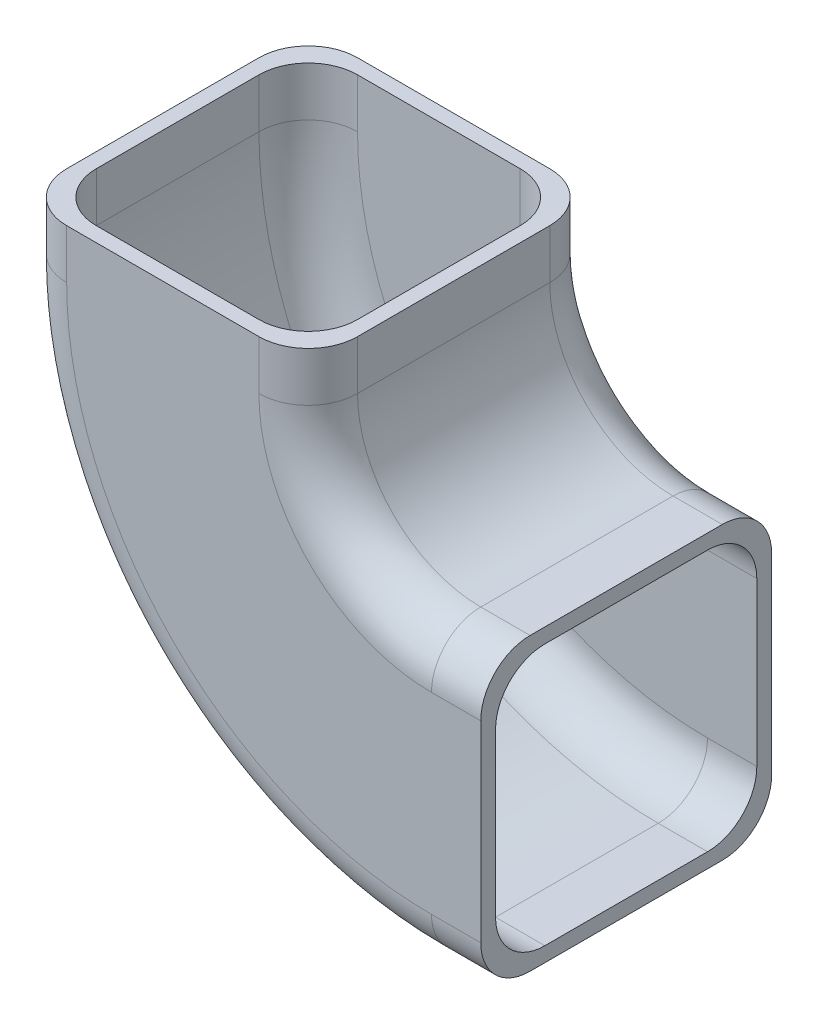
SolidWorks part; units mm, degrees
ref_plane "Front Plane" through (0, 0, 0) normal (0, 0, 1) x (1, 0, 0)
ref_plane "Top Plane" through (0, 0, 0) normal (0, 1, 0) x (1, 0, 0)
ref_plane "Right Plane" through (0, 0, 0) normal (1, 0, 0) x (0, 0, -1)
ref_plane "Plane1" through (0, 0, 26.5) normal (0, 0, 1) x (1, 0, 0)
sketch "Sketch3" plane through (0, 0, 0) normal (0, 0, 1) x (1, 0, 0)
  line L0 (-32.4349, -26.1886) -> (26.5651, -26.1886)
  line L1 (26.5651, -26.1886) -> (26.5651, -36.1886)
  line L2 (-32.4349, -26.1886) -> (-32.4349, -36.1886)
  line L3 (51.5651, -61.1886) -> (61.5651, -61.1886)
  line L4 (51.5651, -120.1886) -> (61.5651, -120.1886)
  line L5 (61.5651, -120.1886) -> (61.5651, -61.1886)
  arc A1 (26.5651, -36.1886) -> (51.5651, -61.1886) centre (51.5651, -36.1886) ccw
  arc A2 (-32.4349, -36.1886) -> (51.5651, -120.1886) centre (51.5651, -36.1886) ccw
  dimension "D3" = 10
  dimension "D1" = 59
  dimension "D2" = 10
extrude "Boss-Extrude3" add sketch "Sketch3" along normal blind 59
sketch "Sketch4" plane through (61.5651, 0, 0) normal (1, 0, 0) x (0, 0, -1)
  line L0 (0, 55) -> (0, -55) construction
  line L1 (-59, -61.1886) -> (0, -61.1886)
  line L2 (-59, -61.1886) -> (-59, -120.1886)
  line L3 (-59, -120.1886) -> (0, -120.1886)
  line L4 (0, -61.1886) -> (0, -120.1886)
  line L5 (-59, -120.1886) -> (0, -120.1886) construction
extrude "Boss-Extrude4" add sketch "Sketch4" along normal blind 100
shell "Shell2" thickness 3
sketch "Sketch5" plane through (161.5651, 0, 0) normal (1, 0, 0) x (0, 0, -1)
  line L5 (0, 55) -> (0, -55) construction
  line L6 (-59, -61.1886) -> (0, -61.1886)
  line L8 (-59, -61.1886) -> (-59, -120.1886)
  line L9 (-59, -120.1886) -> (0, -120.1886)
  line L10 (0, -61.1886) -> (0, -120.1886)
  line L11 (-59, -120.1886) -> (0, -120.1886) construction
extrude "Cut-Extrude1" cut sketch "Sketch5" against normal blind 100
fillet "Fillet1" radius 10 24 edges at (-32.4349, -31.1886, 0) (56.5651, -120.1886, 0) (-32.4349, -31.1886, 59) (56.5651, -120.1886, 59) (26.5651, -31.1886, 59) (33.8874, -53.8662, 59) (56.5651, -61.1886, 0) (26.5651, -31.1886, 0) (-7.8319, -95.5855, 0) (-7.8319, -95.5855, 59) (56.5651, -61.1886, 59) (33.8874, -53.8662, 0) (-29.4349, -31.1886, 56) (56.5651, -117.1886, 56) (56.5651, -64.1886, 56) (31.7661, -55.9876, 56) (-29.4349, -31.1886, 3) (56.5651, -117.1886, 3) (56.5651, -64.1886, 3) (23.5651, -31.1886, 3) (-5.7106, -93.4642, 56) (23.5651, -31.1886, 56) (-5.7106, -93.4642, 3) (31.7661, -55.9876, 3)
